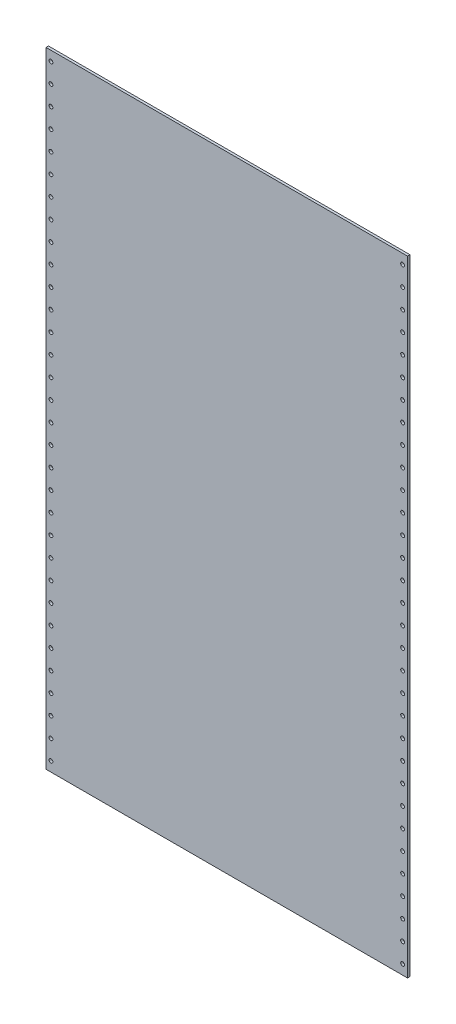
SolidWorks part; units mm, degrees
ref_plane "Front Plane" through (0, 0, 0) normal (0, 0, 1) x (1, 0, 0)
ref_plane "Top Plane" through (0, 0, 0) normal (0, 1, 0) x (1, 0, 0)
ref_plane "Right Plane" through (0, 0, 0) normal (1, 0, 0) x (0, 0, -1)
ref_plane "Plane1" through (0, 0, -1.5875) normal (0, 0, -1) x (-1, 0, 0)
sketch "Sketch1" plane through (0, 0, -1.5875) normal (0, 0, -1) x (-1, 0, 0)
  line L0 (234.95, 406.4) -> (-234.95, 406.4)
  line L1 (-234.95, 406.4) -> (-234.95, -406.4)
  line L2 (-234.95, -406.4) -> (234.95, -406.4)
  line L3 (234.95, -406.4) -> (234.95, 406.4)
  circle A0 centre (-228.6, 393.7) radius 2.5
  circle A1 centre (-228.6, 368.3) radius 2.5
  circle A2 centre (-228.6, 342.9) radius 2.5
  circle A3 centre (-228.6, 317.5) radius 2.5
  circle A4 centre (-228.6, 292.1) radius 2.5
  circle A5 centre (-228.6, 266.7) radius 2.5
  circle A6 centre (-228.6, 241.3) radius 2.5
  circle A7 centre (-228.6, 215.9) radius 2.5
  circle A8 centre (-228.6, 190.5) radius 2.5
  circle A9 centre (-228.6, 165.1) radius 2.5
  circle A10 centre (-228.6, 139.7) radius 2.5
  circle A11 centre (-228.6, 114.3) radius 2.5
  circle A12 centre (-228.6, 88.9) radius 2.5
  circle A13 centre (-228.6, 63.5) radius 2.5
  circle A14 centre (-228.6, 38.1) radius 2.5
  circle A15 centre (-228.6, 12.7) radius 2.5
  circle A16 centre (-228.6, -12.7) radius 2.5
  circle A17 centre (-228.6, -38.1) radius 2.5
  circle A18 centre (-228.6, -63.5) radius 2.5
  circle A19 centre (-228.6, -88.9) radius 2.5
  circle A20 centre (-228.6, -114.3) radius 2.5
  circle A21 centre (-228.6, -139.7) radius 2.5
  circle A22 centre (-228.6, -165.1) radius 2.5
  circle A23 centre (-228.6, -190.5) radius 2.5
  circle A24 centre (-228.6, -215.9) radius 2.5
  circle A25 centre (-228.6, -241.3) radius 2.5
  circle A26 centre (-228.6, -266.7) radius 2.5
  circle A27 centre (-228.6, -292.1) radius 2.5
  circle A28 centre (-228.6, -317.5) radius 2.5
  circle A29 centre (-228.6, -342.9) radius 2.5
  circle A30 centre (-228.6, -368.3) radius 2.5
  circle A31 centre (-228.6, -393.7) radius 2.5
  circle A32 centre (228.6, 393.7) radius 2.5
  circle A33 centre (228.6, 368.3) radius 2.5
  circle A34 centre (228.6, 342.9) radius 2.5
  circle A35 centre (228.6, 317.5) radius 2.5
  circle A36 centre (228.6, 292.1) radius 2.5
  circle A37 centre (228.6, 266.7) radius 2.5
  circle A38 centre (228.6, 241.3) radius 2.5
  circle A39 centre (228.6, 215.9) radius 2.5
  circle A40 centre (228.6, 190.5) radius 2.5
  circle A41 centre (228.6, 165.1) radius 2.5
  circle A42 centre (228.6, 139.7) radius 2.5
  circle A43 centre (228.6, 114.3) radius 2.5
  circle A44 centre (228.6, 88.9) radius 2.5
  circle A45 centre (228.6, 63.5) radius 2.5
  circle A46 centre (228.6, 38.1) radius 2.5
  circle A47 centre (228.6, 12.7) radius 2.5
  circle A48 centre (228.6, -12.7) radius 2.5
  circle A49 centre (228.6, -38.1) radius 2.5
  circle A50 centre (228.6, -63.5) radius 2.5
  circle A51 centre (228.6, -88.9) radius 2.5
  circle A52 centre (228.6, -114.3) radius 2.5
  circle A53 centre (228.6, -139.7) radius 2.5
  circle A54 centre (228.6, -165.1) radius 2.5
  circle A55 centre (228.6, -190.5) radius 2.5
  circle A56 centre (228.6, -215.9) radius 2.5
  circle A57 centre (228.6, -241.3) radius 2.5
  circle A58 centre (228.6, -266.7) radius 2.5
  circle A59 centre (228.6, -292.1) radius 2.5
  circle A60 centre (228.6, -317.5) radius 2.5
  circle A61 centre (228.6, -342.9) radius 2.5
  circle A62 centre (228.6, -368.3) radius 2.5
  circle A63 centre (228.6, -393.7) radius 2.5
extrude "Boss-Extrude1" add sketch "Sketch1" against normal blind 3.175
